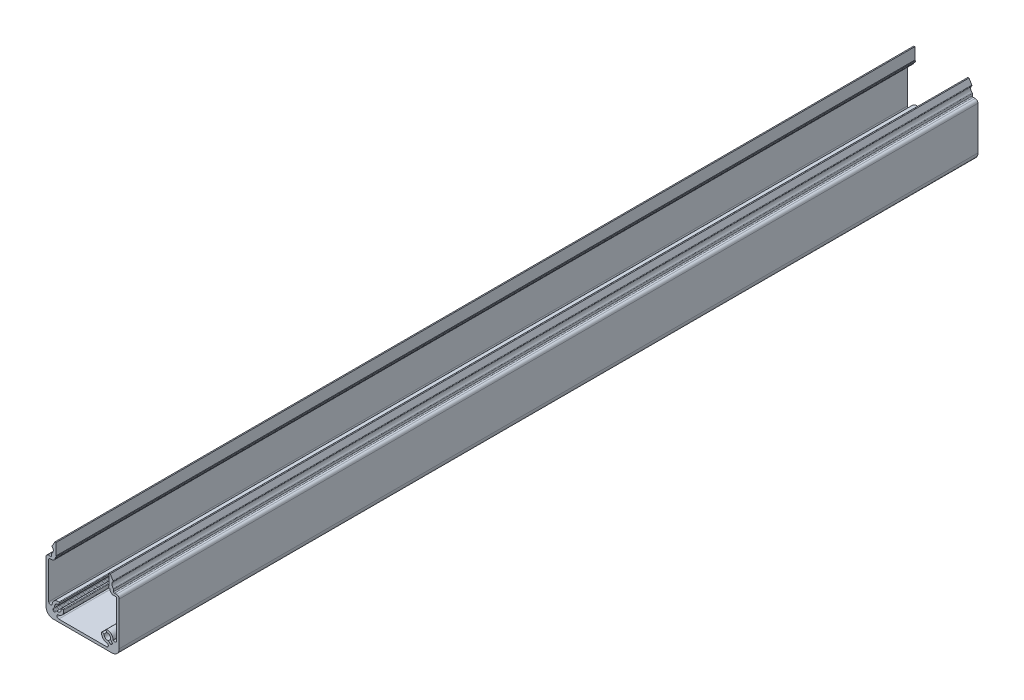
SolidWorks part; units mm, degrees
ref_plane "Front Plane" through (0, 0, 0) normal (0, 0, 1) x (1, 0, 0)
ref_plane "Top Plane" through (0, 0, 0) normal (0, 1, 0) x (1, 0, 0)
ref_plane "Right Plane" through (0, 0, 0) normal (1, 0, 0) x (0, 0, -1)
ref_plane "Plane1" through (0, 0, 20) normal (0, 0, 1) x (1, 0, 0)
sketch "Sketch1" plane through (0, 0, 20) normal (0, 0, 1) x (1, 0, 0)
  line L0 (4, 0) -> (36, 0)
  line L1 (40, 4) -> (40, 27.5)
  line L2 (38.5, 29) -> (37.4085, 29)
  line L3 (36.9085, 29.5) -> (36.9085, 30.572)
  line L4 (36.583, 34.4315) -> (35.1, 37)
  line L5 (35.1, 37) -> (34.5, 37)
  line L6 (34.5, 37) -> (34.5, 30.6727)
  line L7 (34.5, 30.6727) -> (34.1585, 30.5611)
  line L8 (34.1585, 30.5611) -> (34.1585, 29.9899)
  line L9 (34.1585, 29.9899) -> (34.9085, 29.9899)
  line L10 (34.9085, 29.9899) -> (34.9085, 29.7)
  line L11 (36.9085, 27.7) -> (38, 27.7)
  line L12 (38.5, 27.2) -> (38.5, 6.9548)
  line L13 (36.7929, 6.2477) -> (36.6482, 6.3924)
  line L14 (32.7665, 9.2376) -> (33.0471, 8.1904)
  line L15 (35.1484, 5.9123) -> (36.1464, 4.9142)
  line L16 (36.1464, 4.2071) -> (35.7929, 3.8536)
  line L17 (35.0858, 3.8536) -> (34.0877, 4.8516)
  line L18 (31.8096, 6.9529) -> (30.7624, 7.2335)
  line L19 (33.6076, 3.3518) -> (33.7523, 3.2071)
  line L20 (33.0452, 1.5) -> (6.9548, 1.5)
  line L21 (6.2477, 3.2071) -> (6.3924, 3.3518)
  line L22 (9.2376, 7.2335) -> (8.1904, 6.9529)
  line L23 (5.9123, 4.8516) -> (4.9142, 3.8536)
  line L24 (4.2071, 3.8536) -> (3.8536, 4.2071)
  line L25 (3.8536, 4.9142) -> (4.8516, 5.9123)
  line L26 (6.9529, 8.1904) -> (7.2335, 9.2376)
  line L27 (3.3518, 6.3924) -> (3.2071, 6.2477)
  line L28 (1.5, 6.9548) -> (1.5, 27.2)
  line L29 (2, 27.7) -> (3.0915, 27.7)
  line L30 (5.0915, 29.7) -> (5.0915, 29.9899)
  line L31 (5.0915, 29.9899) -> (5.8415, 29.9899)
  line L32 (5.8415, 29.9899) -> (5.8415, 30.5611)
  line L33 (5.8415, 30.5611) -> (5.5, 30.6727)
  line L34 (5.5, 30.6727) -> (5.5, 37)
  line L35 (5.5, 37) -> (4.9, 37)
  line L36 (4.9, 37) -> (3.417, 34.4315)
  line L37 (3.0915, 30.572) -> (3.0915, 29.5)
  line L38 (2.5915, 29) -> (1.5, 29)
  line L39 (0, 27.5) -> (0, 4)
  arc A0 (36, 0) -> (40, 4) centre (36, 4) ccw
  arc A1 (40, 27.5) -> (38.5, 29) centre (38.5, 27.5) ccw
  arc A2 (37.4085, 29) -> (36.9085, 29.5) centre (37.4085, 29.5) cw
  arc A3 (36.9085, 30.572) -> (36.7268, 30.9576) centre (36.4085, 30.572) ccw
  arc A4 (36.7268, 30.9576) -> (36.52, 33.8452) centre (38, 32.5) cw
  arc A5 (36.52, 33.8452) -> (36.583, 34.4315) centre (36.1499, 34.1815) ccw
  arc A6 (34.9085, 29.7) -> (36.9085, 27.7) centre (36.9085, 29.7) ccw
  arc A7 (38, 27.7) -> (38.5, 27.2) centre (38, 27.2) cw
  arc A8 (38.5, 6.9548) -> (36.7929, 6.2477) centre (37.5, 6.9548) cw
  arc A9 (36.6482, 6.3924) -> (33.0095, 9.6116) centre (33.5, 6.5) ccw
  arc A10 (33.0095, 9.6116) -> (32.7665, 9.2376) centre (33.0562, 9.3152) ccw
  arc A11 (33.0471, 8.1904) -> (35.1484, 5.9123) centre (33.5, 6.5) cw
  arc A12 (36.1464, 4.9142) -> (36.1464, 4.2071) centre (35.7929, 4.5607) cw
  arc A13 (35.7929, 3.8536) -> (35.0858, 3.8536) centre (35.4393, 4.2071) cw
  arc A14 (34.0877, 4.8516) -> (31.8096, 6.9529) centre (33.5, 6.5) cw
  arc A15 (30.7624, 7.2335) -> (30.3884, 6.9905) centre (30.6848, 6.9438) ccw
  arc A16 (30.3884, 6.9905) -> (33.6076, 3.3518) centre (33.5, 6.5) ccw
  arc A17 (33.7523, 3.2071) -> (33.0452, 1.5) centre (33.0452, 2.5) cw
  arc A18 (6.9548, 1.5) -> (6.2477, 3.2071) centre (6.9548, 2.5) cw
  arc A19 (6.3924, 3.3518) -> (9.6116, 6.9905) centre (6.5, 6.5) ccw
  arc A20 (9.6116, 6.9905) -> (9.2376, 7.2335) centre (9.3152, 6.9438) ccw
  arc A21 (8.1904, 6.9529) -> (5.9123, 4.8516) centre (6.5, 6.5) cw
  arc A22 (4.9142, 3.8536) -> (4.2071, 3.8536) centre (4.5607, 4.2071) cw
  arc A23 (3.8536, 4.2071) -> (3.8536, 4.9142) centre (4.2071, 4.5607) cw
  arc A24 (4.8516, 5.9123) -> (6.9529, 8.1904) centre (6.5, 6.5) cw
  arc A25 (7.2335, 9.2376) -> (6.9905, 9.6116) centre (6.9438, 9.3152) ccw
  arc A26 (6.9905, 9.6116) -> (3.3518, 6.3924) centre (6.5, 6.5) ccw
  arc A27 (3.2071, 6.2477) -> (1.5, 6.9548) centre (2.5, 6.9548) cw
  arc A28 (1.5, 27.2) -> (2, 27.7) centre (2, 27.2) cw
  arc A29 (3.0915, 27.7) -> (5.0915, 29.7) centre (3.0915, 29.7) ccw
  arc A30 (3.417, 34.4315) -> (3.48, 33.8452) centre (3.8501, 34.1815) ccw
  arc A31 (3.48, 33.8452) -> (3.2732, 30.9576) centre (2, 32.5) cw
  arc A32 (3.2732, 30.9576) -> (3.0915, 30.572) centre (3.5915, 30.572) ccw
  arc A33 (3.0915, 29.5) -> (2.5915, 29) centre (2.5915, 29.5) cw
  arc A34 (1.5, 29) -> (0, 27.5) centre (1.5, 27.5) ccw
  arc A35 (0, 4) -> (4, 0) centre (4, 4) ccw
extrude "Boss-Extrude1" add sketch "Sketch1" against normal blind 469
